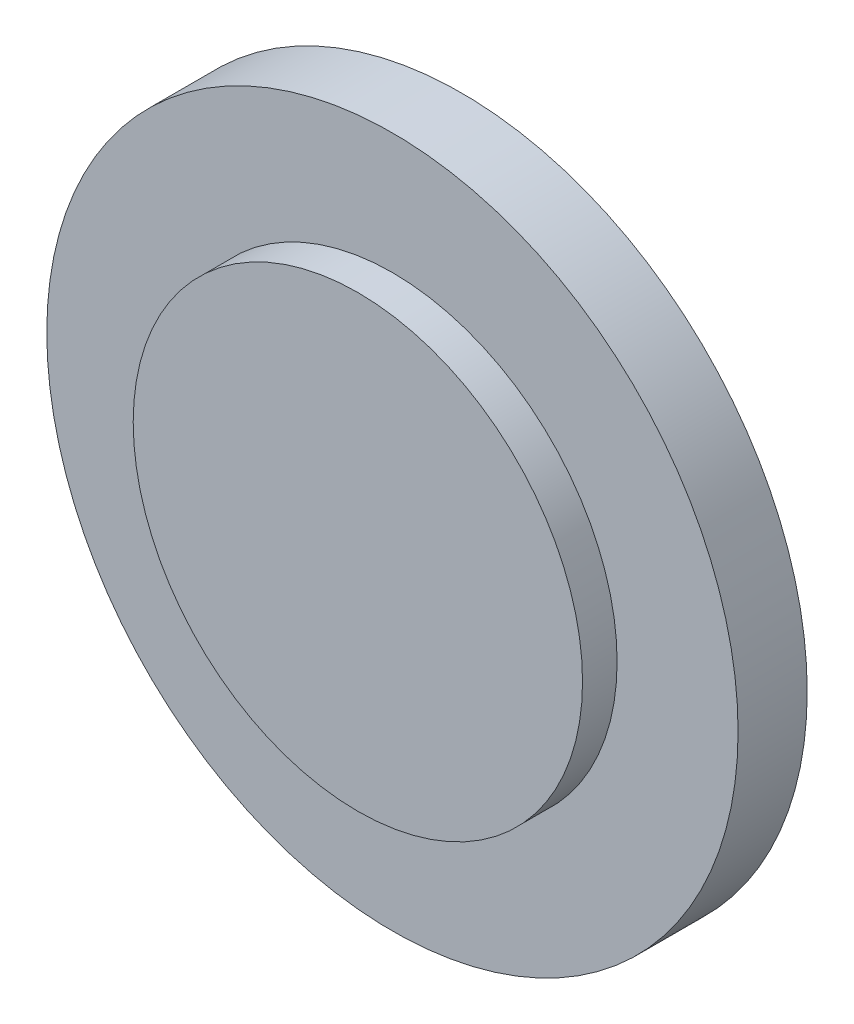
SolidWorks part; units mm, degrees
ref_plane "Front Plane" through (0, 0, 0) normal (0, 0, 1) x (1, 0, 0)
ref_plane "Top Plane" through (0, 0, 0) normal (0, 1, 0) x (1, 0, 0)
ref_plane "Right Plane" through (0, 0, 0) normal (1, 0, 0) x (0, 0, -1)
sketch "Sketch1" plane through (0, 0, 0) normal (0, 0, 1) x (1, 0, 0)
  circle A0 centre (0, 0) radius 5
  dimension "D1" = 10
extrude "Boss-Extrude1" add sketch "Sketch1" along normal blind 1
sketch "Sketch2" plane through (0, 0, 1) normal (0, 0, 1) x (1, 0, 0)
  circle A0 centre (0, 0) radius 3.25
  dimension "D1" = 6.5
extrude "Boss-Extrude2" add sketch "Sketch2" along normal blind 0.5
